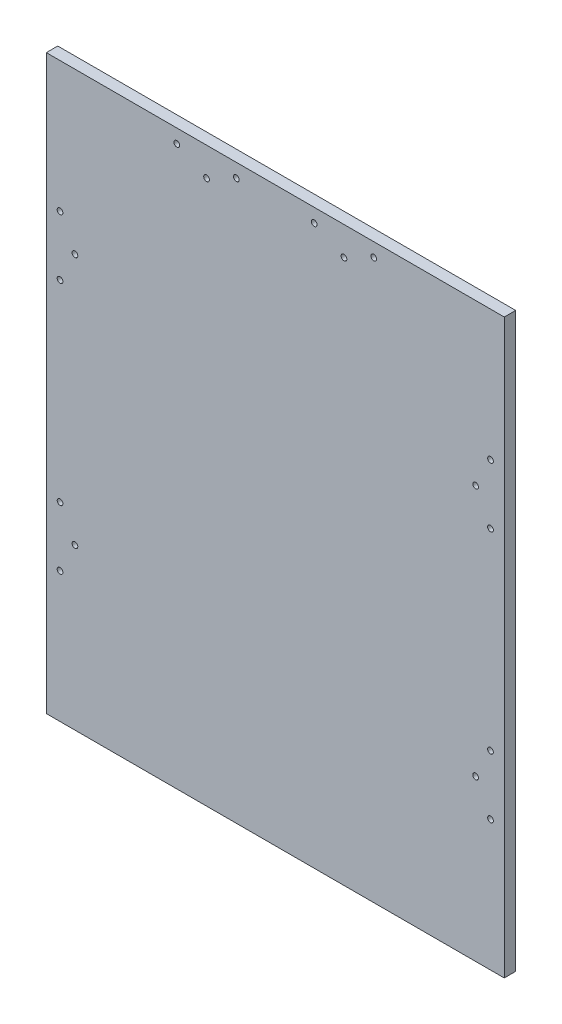
SolidWorks part; units mm, degrees
ref_plane "Front Plane" through (0, 0, 0) normal (0, 0, 1) x (1, 0, 0)
ref_plane "Top Plane" through (0, 0, 0) normal (0, 1, 0) x (1, 0, 0)
ref_plane "Right Plane" through (0, 0, 0) normal (1, 0, 0) x (0, 0, -1)
sketch "Sketch1" plane through (0, 0, 0) normal (0, 0, 1) x (1, 0, 0)
  line L1 (200, -250) -> (-200, -250)
  line L2 (200, -250) -> (200, 250)
  line L3 (200, 250) -> (-200, 250)
  line L4 (-200, -250) -> (-200, 250)
  line L5 (200, -250) -> (-200, 250) construction
  line L6 (200, 250) -> (-200, -250) construction
  point P0 (0, 0)
  dimension "D1" = 400
  dimension "D2" = 500
extrude "Boss-Extrude1" add sketch "Sketch1" along normal blind 10
sketch "Sketch2" plane through (0, 0, 10) normal (0, 0, 1) x (1, 0, 0)
  line L2 (-200, -250) -> (200, -250) construction
  line L3 (-200, 250) -> (-200, -250) construction
  line L4 (200, 250) -> (-200, 250) construction
  line L5 (200, -250) -> (200, 250) construction
  circle A0 centre (-188, -136) radius 2.5
  circle A1 centre (-175, -110) radius 2.5
  circle A2 centre (-188, -84) radius 2.5
  circle A3 centre (-188, 136) radius 2.5
  circle A4 centre (-175, 110) radius 2.5
  circle A5 centre (-188, 84) radius 2.5
  circle A6 centre (-86, 238) radius 2.5
  circle A7 centre (-60, 225) radius 2.5
  circle A8 centre (-34, 238) radius 2.5
  circle A9 centre (34, 238) radius 2.5
  circle A10 centre (60, 225) radius 2.5
  circle A11 centre (86, 238) radius 2.5
  circle A12 centre (175, 110) radius 2.5
  circle A13 centre (188, 136) radius 2.5
  circle A14 centre (188, 84) radius 2.5
  circle A15 centre (188, -84) radius 2.5
  circle A16 centre (175, -110) radius 2.5
  circle A17 centre (188, -136) radius 2.5
  dimension "D1" = 114
  dimension "D2" = 12
  dimension "D3" = 140
  dimension "D4" = 25
  dimension "D5" = 12
  dimension "D6" = 166
  dimension "D7" = 12
  dimension "D8" = 114
  dimension "D9" = 140
  dimension "D10" = 25
  dimension "D11" = 166
  dimension "D12" = 12
  dimension "D13" = 114
  dimension "D14" = 12
  dimension "D15" = 140
  dimension "D16" = 25
  dimension "D17" = 12
  dimension "D18" = 166
  dimension "D19" = 12
  dimension "D20" = 114
  dimension "D21" = 140
  dimension "D22" = 25
  dimension "D23" = 166
  dimension "D24" = 12
  dimension "D25" = 12
  dimension "D26" = 114
  dimension "D27" = 140
  dimension "D28" = 25
  dimension "D29" = 166
  dimension "D30" = 12
  dimension "D31" = 114
  dimension "D32" = 12
  dimension "D33" = 140
  dimension "D34" = 25
  dimension "D35" = 166
  dimension "D36" = 12
extrude "Cut-Extrude1" cut sketch "Sketch2" against normal through all
sketch "Sketch3" plane through (0, -250, 0) normal (0, -1, 0) x (1, 0, 0)
  line L0 (-200, 0) -> (200, 0) construction
  line L1 (-200, 10) -> (-200, 0) construction
  line L2 (200, 10) -> (200, 0) construction
  circle A0 centre (-20.25, 5) radius 2.5
  circle A1 centre (20.25, 5) radius 2.5
  dimension "D1" = 5
  dimension "D3" = 5
  dimension "D4" = 179.75
  dimension "D2" = 179.75
extrude "Cut-Extrude2" cut sketch "Sketch3" against normal blind 10
